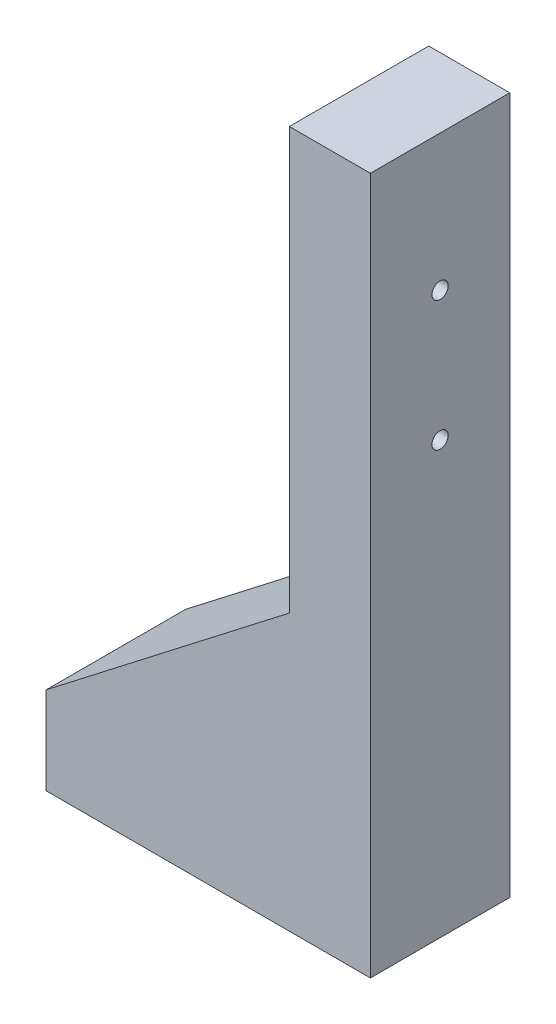
SolidWorks part; units mm, degrees
material "Beech"
ref_plane "Front Plane" through (0, 0, 0) normal (0, 0, 1) x (1, 0, 0)
ref_plane "Top Plane" through (0, 0, 0) normal (0, 1, 0) x (1, 0, 0)
ref_plane "Right Plane" through (0, 0, 0) normal (1, 0, 0) x (0, 0, -1)
sketch "Sketch1" plane through (0, 0, 0) normal (0, 0, 1) x (1, 0, 0)
  line L0 (0, 0) -> (0, 130)
  line L1 (0, 130) -> (25, 130)
  line L2 (25, 130) -> (25, -85)
  line L3 (25, -85) -> (-75, -85)
  line L4 (-75, -85) -> (-75, -58)
  line L5 (-75, -58) -> (0, 0)
  dimension "D1" = 130
  dimension "D2" = 25
  dimension "D3" = 215
  dimension "D4" = 100
  dimension "D5" = 27
extrude "Boss-Extrude1" add sketch "Sketch1" along normal blind 43
sketch "Sketch2" plane through (0, 0, 0) normal (-1, 0, 0) x (0, 0, 1)
  line L0 (21.5, 130) -> (21.5, 0) construction
  line L1 (43, 130) -> (0, 130) construction
  line L2 (43, 0) -> (0, 0) construction
  circle A0 centre (21.5, 88) radius 2.5
  circle A1 centre (21.5, 48) radius 2.5
  dimension "D1" = 5
  dimension "D2" = 42
  dimension "D3" = 5
  dimension "D4" = 82
extrude "Cut-Extrude1" cut sketch "Sketch2" against normal blind 25
